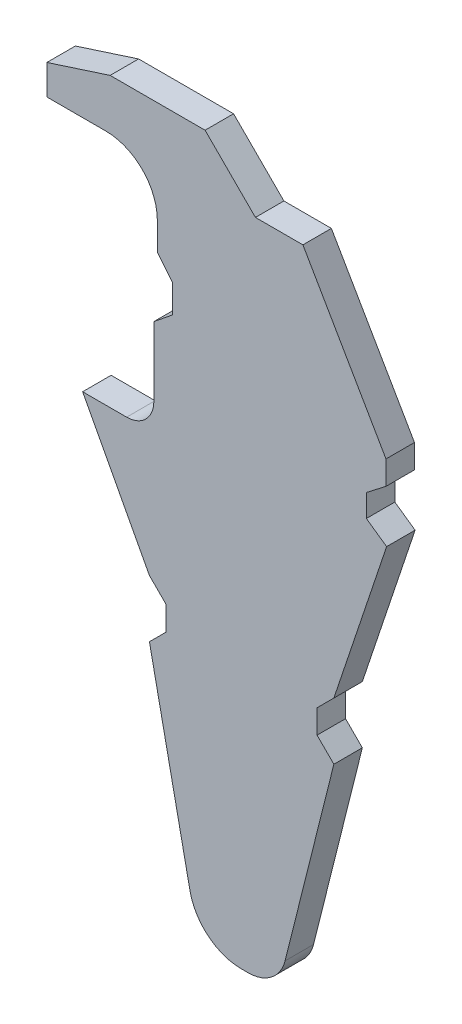
SolidWorks part; units mm, degrees
ref_plane "Front Plane" through (0, 0, 0) normal (0, 0, 1) x (1, 0, 0)
ref_plane "Top Plane" through (0, 0, 0) normal (0, 1, 0) x (1, 0, 0)
ref_plane "Right Plane" through (0, 0, 0) normal (1, 0, 0) x (0, 0, -1)
sketch "Sketch1" plane through (0, 0, 0) normal (0, 0, 1) x (1, 0, 0)
  line L1 (-53.9725, 62.2722) -> (-33.9725, 62.2722)
  line L2 (-33.9725, 62.2722) -> (-23.3659, 51.6656)
  line L3 (-23.3659, 51.6656) -> (-13.3659, 51.6656)
  line L4 (-13.3659, 51.6656) -> (4.1341, 21.3547)
  line L5 (4.1341, 21.3547) -> (4.1341, 16.3547)
  line L6 (4.1341, 16.3547) -> (0, 13.1644)
  line L7 (0, 13.1644) -> (0, 8.423)
  line L8 (0, 8.423) -> (4.2715, 5.4321)
  line L9 (4.2715, 5.4321) -> (-6.8453, -27.7555)
  line L10 (-6.8453, -27.7555) -> (-10.3809, -31.291)
  line L11 (-10.3809, -31.291) -> (-10.3809, -36.291)
  line L12 (-10.3809, -36.291) -> (-6.8453, -39.8266)
  line L13 (-6.8453, -39.8266) -> (-17.1237, -80.8444)
  line L14 (-24.8838, -86.8998) -> (-26.3108, -86.8998)
  line L15 (-37.1407, -78.0878) -> (-45.6939, -36.8998)
  line L16 (-45.6939, -36.8998) -> (-42.1584, -33.3643)
  line L17 (-42.1584, -33.3643) -> (-42.1584, -28.3643)
  line L18 (-42.1584, -28.3643) -> (-45.6939, -24.8287)
  line L19 (-45.6939, -24.8287) -> (-59.7669, 1.6656)
  line L20 (-59.7669, 1.6656) -> (-50.4944, 1.6656)
  line L21 (-44.7669, 7.393) -> (-44.7669, 21.9615)
  line L22 (-44.7669, 21.9615) -> (-40.8811, 25.108)
  line L23 (-40.8811, 25.108) -> (-40.8811, 31.108)
  line L24 (-40.8811, 31.108) -> (-44.0276, 34.9938)
  line L26 (-67.2955, 57.9712) -> (-53.9725, 62.2722)
  line L27 (-67.2955, 57.9712) -> (-67.2955, 51.6656)
  line L28 (-67.2955, 51.6656) -> (-54.8709, 51.6656)
  line L29 (-44.0276, 40.8223) -> (-44.0276, 34.9938)
  arc A0 (-17.1237, -80.8444) -> (-24.8838, -86.8998) centre (-24.8838, -78.8998) cw
  arc A1 (-37.1407, -78.0878) -> (-26.3108, -86.8998) centre (-26.3108, -75.8388) ccw
  arc A2 (-44.7669, 7.393) -> (-50.4944, 1.6656) centre (-50.4944, 7.393) cw
  arc A3 (-54.8709, 51.6656) -> (-44.0276, 40.8223) centre (-54.8709, 40.8223) cw
extrude "Boss-Extrude1" add sketch "Sketch1" along normal blind 6
